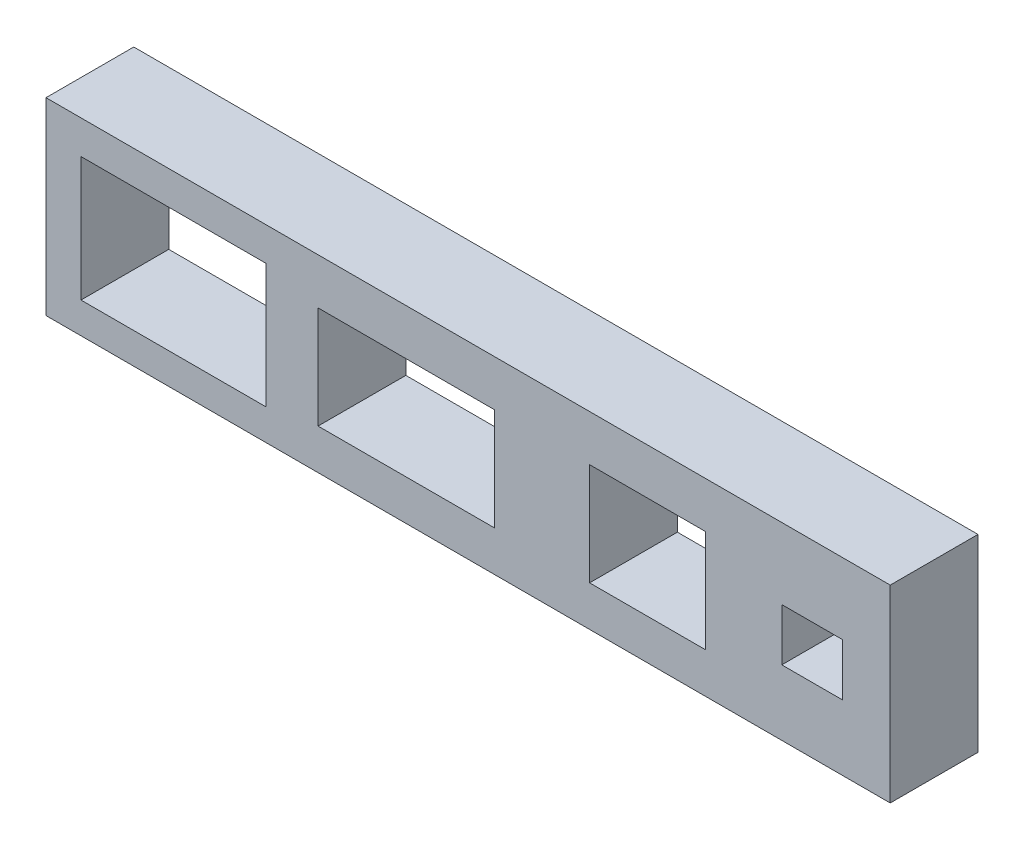
SolidWorks part; units mm, degrees
ref_plane "Front Plane" through (0, 0, 0) normal (0, 0, 1) x (1, 0, 0)
ref_plane "Top Plane" through (0, 0, 0) normal (0, 1, 0) x (1, 0, 0)
ref_plane "Right Plane" through (0, 0, 0) normal (1, 0, 0) x (0, 0, -1)
sketch "Sketch1" plane through (0, 0, 0) normal (0, 0, 1) x (1, 0, 0)
  line L1 (0, 0) -> (96.1748, 0)
  line L2 (0, 0) -> (0, 21.5004)
  line L3 (0, 21.5004) -> (96.1748, 21.5004)
  line L4 (96.1748, 0) -> (96.1748, 21.5004)
  line L5 (3.9859, 17.6861) -> (25.0454, 17.6861)
  line L6 (3.9859, 17.6861) -> (3.9859, 3.5274)
  line L7 (3.9859, 3.5274) -> (25.0454, 3.5274)
  line L8 (25.0454, 17.6861) -> (25.0454, 3.5274)
  line L9 (30.9944, 16.2583) -> (51.1021, 16.2583)
  line L10 (30.9944, 16.2583) -> (30.9944, 4.5982)
  line L11 (30.9944, 4.5982) -> (51.1021, 4.5982)
  line L12 (51.1021, 16.2583) -> (51.1021, 4.5982)
  line L13 (61.9293, 16.2583) -> (75.1361, 16.2583)
  line L14 (61.9293, 16.2583) -> (61.9293, 4.5982)
  line L15 (61.9293, 4.5982) -> (75.1361, 4.5982)
  line L16 (75.1361, 16.2583) -> (75.1361, 4.5982)
  line L17 (83.8217, 13.4028) -> (90.7225, 13.4028)
  line L18 (83.8217, 13.4028) -> (83.8217, 7.4538)
  line L19 (83.8217, 7.4538) -> (90.7225, 7.4538)
  line L20 (90.7225, 13.4028) -> (90.7225, 7.4538)
extrude "Boss-Extrude1" add sketch "Sketch1" along normal blind 10
